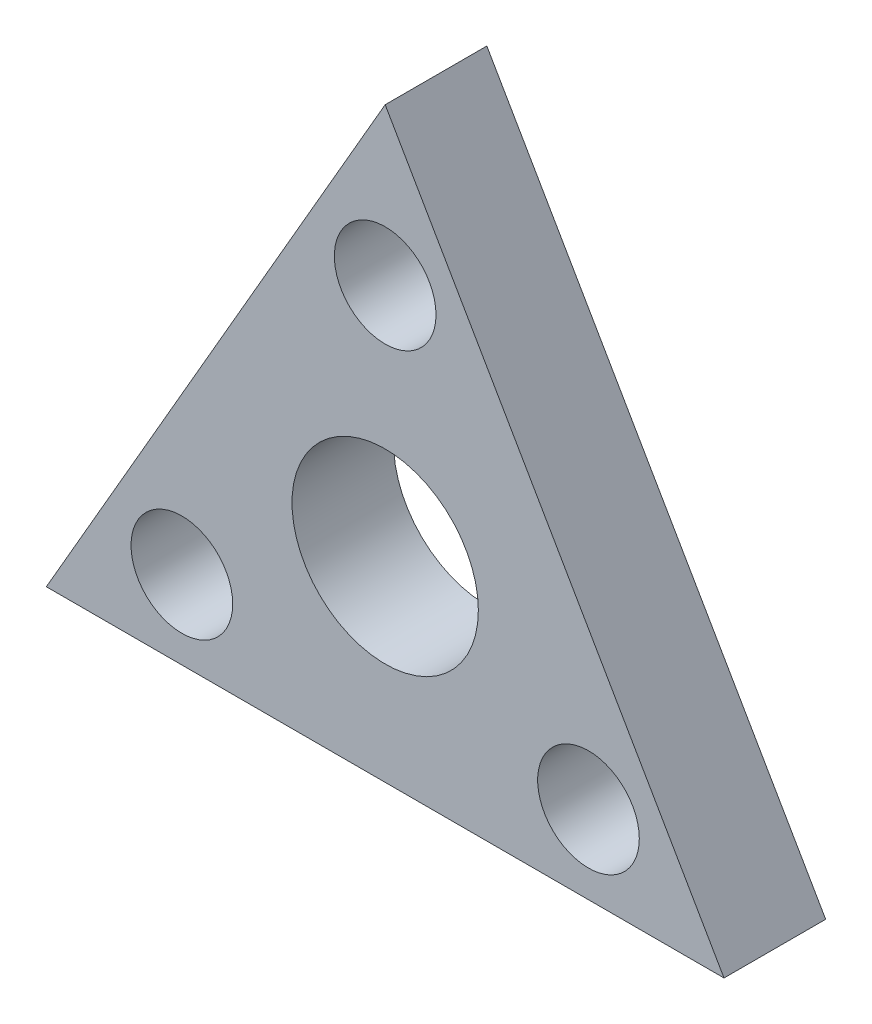
SolidWorks part; units mm, degrees
ref_plane "前视基准面" through (0, 0, 0) normal (0, 0, 1) x (1, 0, 0)
ref_plane "上视基准面" through (0, 0, 0) normal (0, 1, 0) x (1, 0, 0)
ref_plane "右视基准面" through (0, 0, 0) normal (1, 0, 0) x (0, 0, -1)
other "Configuration Table"
sketch "草图1" plane through (0, 0, 0) normal (0, 0, 1) x (1, 0, 0)
  line L1 (0, 11.547) -> (-10, -5.7735)
  line L2 (-10, -5.7735) -> (10, -5.7735)
  line L3 (10, -5.7735) -> (0, 11.547)
  line L4 (0, 6.9282) -> (-6, -3.4641) construction
  line L5 (-6, -3.4641) -> (6, -3.4641) construction
  line L6 (6, -3.4641) -> (0, 6.9282) construction
  circle A0 centre (0, 0) radius 5.7735 construction
  circle A1 centre (0, 0) radius 3.4641 construction
  circle A2 centre (0, 6.9282) radius 1.5
  circle A3 centre (-6, -3.4641) radius 1.5
  circle A4 centre (6, -3.4641) radius 1.5
  circle A5 centre (0, 0) radius 2.75
  dimension "D3" = 3
  dimension "D4" = 5.5
  dimension "D1" = 20
  dimension "D2" = 12
extrude "凸台-拉伸1" add sketch "草图1" along normal blind 3
